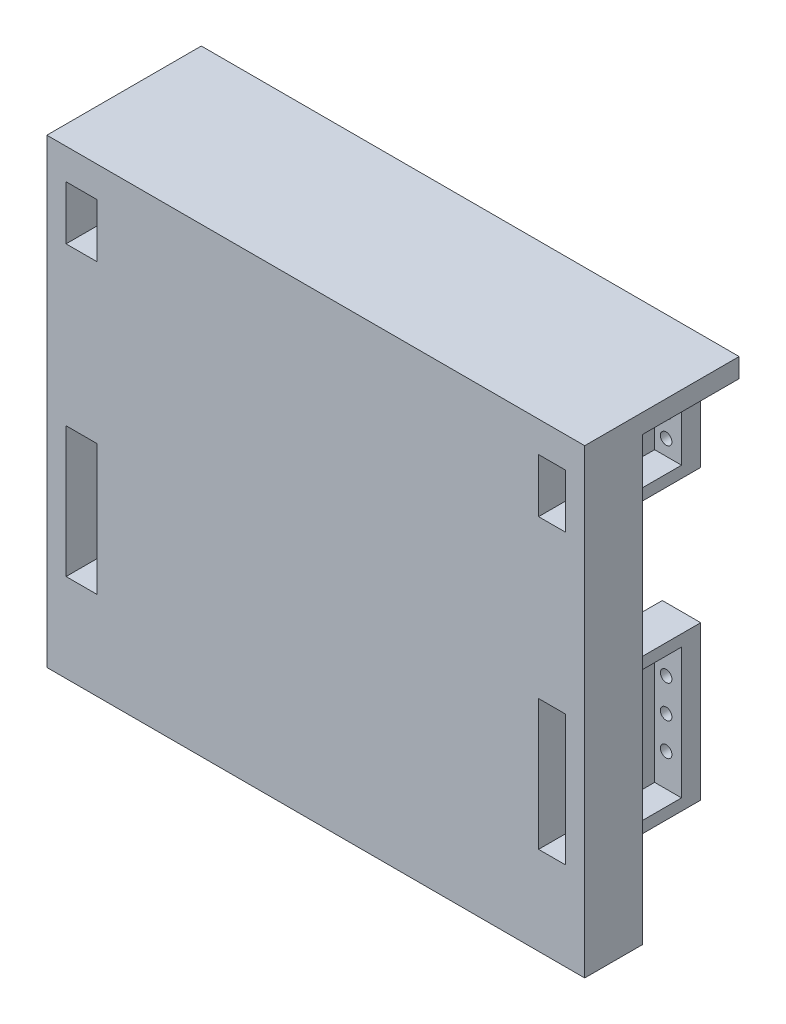
SolidWorks part; units mm, degrees
ref_plane "정면" through (0, 0, 0) normal (0, 0, 1) x (1, 0, 0)
ref_plane "윗면" through (0, 0, 0) normal (0, 1, 0) x (1, 0, 0)
ref_plane "우측면" through (0, 0, 0) normal (1, 0, 0) x (0, 0, -1)
sketch "스케치1" plane through (0, 0, 0) normal (0, 0, 1) x (1, 0, 0)
  line L1 (-64.9056, 62.0253) -> (75.0944, 62.0253)
  line L2 (-64.9056, 62.0253) -> (-64.9056, -57.9747)
  line L3 (-64.9056, -57.9747) -> (75.0944, -57.9747)
  line L4 (75.0944, 62.0253) -> (75.0944, -57.9747)
  dimension "D1" = 140
  dimension "D2" = 120
extrude "보스-돌출1" add sketch "스케치1" along normal blind 5
sketch "스케치2" plane through (0, 0, 0) normal (0, 0, -1) x (-1, 0, 0)
  line L0 (64.9056, 62.0253) -> (64.9056, -57.9747) construction
  line L1 (-75.0944, 62.0253) -> (64.9056, 62.0253)
  line L2 (-75.0944, 62.0253) -> (-75.0944, 57.0253)
  line L3 (-75.0944, 57.0253) -> (64.9056, 57.0253)
  line L4 (64.9056, 62.0253) -> (64.9056, 57.0253)
  dimension "D1" = 5
extrude "보스-돌출2" add sketch "스케치2" along normal blind 35.2
sketch "스케치4" plane through (0, 0, -35.2) normal (0, 0, -1) x (-1, 0, 0)
  line L0 (-5.0944, 62.0253) -> (-5.0944, -57.9747)
  line L1 (64.9056, 62.0253) -> (-75.0944, 62.0253) construction
  line L2 (64.9056, -57.9747) -> (-75.0944, -57.9747) construction
sketch "스케치5" plane through (0, 0, 0) normal (0, 0, -1) x (-1, 0, 0)
  line L0 (-5.0944, -57.9747) -> (-5.0944, 57.0253)
  line L1 (64.9056, -57.9747) -> (-75.0944, -57.9747) construction
  line L2 (-75.0944, 57.0253) -> (64.9056, 57.0253) construction
  line L4 (-60.0944, 2.0253) -> (-70.0944, 2.0253)
  line L5 (-60.0944, 2.0253) -> (-60.0944, -37.9747)
  line L6 (-60.0944, -37.9747) -> (-70.0944, -37.9747)
  line L7 (-70.0944, 2.0253) -> (-70.0944, -37.9747)
  line L9 (49.9056, 2.0253) -> (49.9056, -37.9747)
  line L10 (49.9056, -37.9747) -> (59.9056, -37.9747)
  line L11 (59.9056, 2.0253) -> (59.9056, -37.9747)
  line L12 (49.9056, 2.0253) -> (59.9056, 2.0253)
  line L13 (49.9056, 57.0253) -> (49.9056, 37.0253)
  line L14 (-70.0944, 57.0253) -> (-60.0944, 57.0253)
  line L15 (-70.0944, 57.0253) -> (-70.0944, 37.0253)
  line L16 (-70.0944, 37.0253) -> (-60.0944, 37.0253)
  line L17 (-60.0944, 57.0253) -> (-60.0944, 37.0253)
  line L18 (59.9056, 37.0253) -> (49.9056, 37.0253)
  line L19 (59.9056, 57.0253) -> (59.9056, 37.0253)
  line L20 (59.9056, 57.0253) -> (49.9056, 57.0253)
  line L21 (59.9056, 2.0253) -> (59.9056, -37.9747)
  line L22 (49.9056, -37.9747) -> (59.9056, -37.9747)
  line L23 (49.9056, 2.0253) -> (49.9056, -37.9747)
  line L24 (49.9056, 2.0253) -> (59.9056, 2.0253)
  line M1 (64.9056, 57.0253) -> (-75.0944, 57.0253)
  dimension "D1" = 55
  dimension "D2" = 10
  dimension "D3" = 40
  dimension "D4" = 55
  dimension "D5" = 20
  dimension "D6" = 10
extrude "보스-돌출3" add sketch "스케치5" along normal blind 30.2 contours L4 L7 L6 L5 | L17 L15 L16 M1 | L12 L9 L10 L11 | L19 L18 L13 L20
sketch "스케치6" plane through (0, 0, 5) normal (0, 0, 1) x (1, 0, 0)
  line L1 (60.0944, 2.0253) -> (70.0944, 2.0253)
  line L2 (60.0944, 2.0253) -> (60.0944, -37.9747)
  line L3 (60.0944, -37.9747) -> (70.0944, -37.9747)
  line L4 (70.0944, 2.0253) -> (70.0944, -37.9747)
  line L5 (70.0944, 2.0253) -> (70.0944, -37.9747) construction
  line L6 (60.0944, 2.0253) -> (70.0944, 2.0253) construction
  line L7 (60.0944, 2.0253) -> (60.0944, -37.9747) construction
  line L8 (60.0944, -37.9747) -> (70.0944, -37.9747) construction
  line L9 (70.0944, 37.0253) -> (60.0944, 37.0253) construction
  line L10 (60.0944, 57.0253) -> (70.0944, 57.0253)
  line L11 (60.0944, 57.0253) -> (60.0944, 37.0253)
  line L12 (60.0944, 37.0253) -> (70.0944, 37.0253)
  line L13 (70.0944, 57.0253) -> (70.0944, 37.0253)
  line L14 (70.0944, 57.0253) -> (70.0944, 37.0253) construction
  line L16 (75.0944, 57.0253) -> (-64.9056, 57.0253) construction
  line L17 (60.0944, 57.0253) -> (60.0944, 37.0253) construction
  line L18 (5.0944, 62.0253) -> (5.0944, -57.9747)
  line L19 (75.0944, 62.0253) -> (-64.9056, 62.0253) construction
  line L20 (-64.9056, -57.9747) -> (75.0944, -57.9747) construction
  line L21 (-59.9056, 57.0253) -> (-59.9056, 37.0253)
  line L22 (-49.9056, 37.0253) -> (-59.9056, 37.0253)
  line L23 (-49.9056, 57.0253) -> (-49.9056, 37.0253)
  line L24 (-49.9056, 57.0253) -> (-59.9056, 57.0253)
  line L25 (-59.9056, 2.0253) -> (-59.9056, -37.9747)
  line L26 (-49.9056, -37.9747) -> (-59.9056, -37.9747)
  line L27 (-49.9056, 2.0253) -> (-49.9056, -37.9747)
  line L28 (-49.9056, 2.0253) -> (-59.9056, 2.0253)
  line L29 (-51.9056, 57.0253) -> (-51.9056, 37.0253)
  line L30 (-51.9056, 37.0253) -> (-51.9056, 2.0253)
  line L31 (-51.9056, 2.0253) -> (-51.9056, -37.9747)
  line L32 (63.0944, 57.0253) -> (63.0944, -37.9747)
  line L33 (-59.9056, 54.0253) -> (75.0944, 54.0253)
  line L34 (75.0944, -57.9747) -> (75.0944, 62.0253) construction
  line L35 (-59.9056, 40.0253) -> (75.0944, 40.0253)
  line L36 (-59.9056, -34.9747) -> (70.0944, -34.9747)
  line L37 (-59.9056, -0.9747) -> (63.6225, -0.9747)
  line L38 (-64.9056, 62.0253) -> (75.0944, 62.0253) construction
  line L39 (63.6225, -0.9747) -> (75.0944, -0.9747)
  dimension "D1" = 8
  dimension "D2" = 3
  dimension "D3" = 3
  dimension "D4" = 3
  dimension "D5" = 3
  dimension "D6" = 3
extrude "컷-돌출1" cut sketch "스케치6" against normal blind 30.2 contours L21 L35 L29 L33 | L37 L25 L36 L31 | L39 L37 L32 L36 L4 | L32 L35 L13 L33
sketch "스케치8" plane through (0, 0, -25.2) normal (0, 0, 1) x (1, 0, 0)
  line L0 (-59.9056, 54.0253) -> (-51.9056, 54.0253)
  line L1 (-59.9056, 54.0253) -> (-51.9056, 54.0253) construction
  line L2 (-55.9056, 54.0253) -> (-55.9056, -34.9747)
  line L3 (-59.9056, -34.9747) -> (-51.9056, -34.9747) construction
  line L4 (-59.9056, 54.0253) -> (-59.9056, 40.0253) construction
  line L5 (66.0944, 54.0253) -> (66.0944, -34.9747)
  line L6 (63.0944, 54.0253) -> (70.0944, 54.0253) construction
  line L7 (63.0944, -34.9747) -> (70.0944, -34.9747) construction
  line L10 (-59.9056, 40.0253) -> (-51.9056, 40.0253) construction
  line L12 (-51.9056, -0.9747) -> (-51.9056, -34.9747)
  line L13 (-59.9056, -0.9747) -> (-51.9056, -0.9747) construction
  line L14 (5.0944, -60.3584) -> (5.0944, 68.2675)
  line L15 (5.0944, 62.0253) -> (5.0944, -57.9747) construction
  line L16 (62.0944, -0.9747) -> (62.0944, -34.9747)
  line L17 (66.0944, 54.0253) -> (66.0944, -34.9747)
  line L18 (70.0944, 54.0253) -> (62.0944, 54.0253)
  circle A0 centre (-55.9056, 50.0253) radius 1.5
  circle A1 centre (-55.9056, 44.0253) radius 1.5
  circle A2 centre (-55.9056, -9.4747) radius 1.5
  circle A3 centre (-55.9056, -17.9747) radius 1.5
  circle A4 centre (-55.9056, -26.4747) radius 1.5
  circle A5 centre (66.0944, -26.4747) radius 1.5
  circle A6 centre (66.0944, -17.9747) radius 1.5
  circle A7 centre (66.0944, -9.4747) radius 1.5
  circle A8 centre (66.0944, 44.0253) radius 1.5
  circle A9 centre (66.0944, 50.0253) radius 1.5
  dimension "D3" = 3
  dimension "D4" = 3
  dimension "D7" = 3
  dimension "D8" = 3
  dimension "D9" = 3
  dimension "D10" = 8.5
  dimension "D11" = 8.5
  dimension "D12" = 8.5
  dimension "D1" = 4
  dimension "D5" = 4
  dimension "D6" = 4
extrude "컷-돌출2" cut sketch "스케치8" against normal through all contours L2 A1 | L2 A1 | L2 A0 | L2 A0 | L2 A2 | L2 A2 | L2 A3 | L2 A3 | L2 A4 | L2 A4 | A5 L17 | A5 L17 | A6 L17 | A6 L17 | A7 L17 | A7 L17 | A8 L17 | A8 L17 | A9 L17 | A9 L17
sketch "스케치9" plane through (0, 0, 5) normal (0, 0, 1) x (1, 0, 0)
  line L0 (-64.9056, -57.9747) -> (75.0944, -57.9747)
  line L1 (-64.9056, 57.0253) -> (75.0944, 57.0253)
  line L2 (-64.9056, 62.0253) -> (-64.9056, -57.9747) construction
  line L3 (75.0944, -57.9747) -> (75.0944, 62.0253) construction
  line L4 (75.0944, 57.0253) -> (70.0944, 57.0253) construction
sketch "스케치11" plane through (0, 0, 0) normal (0, 0, -1) x (-1, 0, 0)
  line L1 (64.9056, -57.9747) -> (59.9056, -57.9747)
  line L2 (64.9056, -57.9747) -> (64.9056, 57.0253)
  line L3 (64.9056, 57.0253) -> (59.9056, 57.0253)
  line L4 (59.9056, -57.9747) -> (59.9056, 57.0253)
  line L5 (-75.0944, -57.9747) -> (-70.0944, -57.9747)
  line L6 (-75.0944, -57.9747) -> (-75.0944, 57.0253)
  line L7 (-75.0944, 57.0253) -> (-70.0944, 57.0253)
  line L8 (-70.0944, -57.9747) -> (-70.0944, 57.0253)
extrude "보스-돌출4" add sketch "스케치11" along normal blind 10
